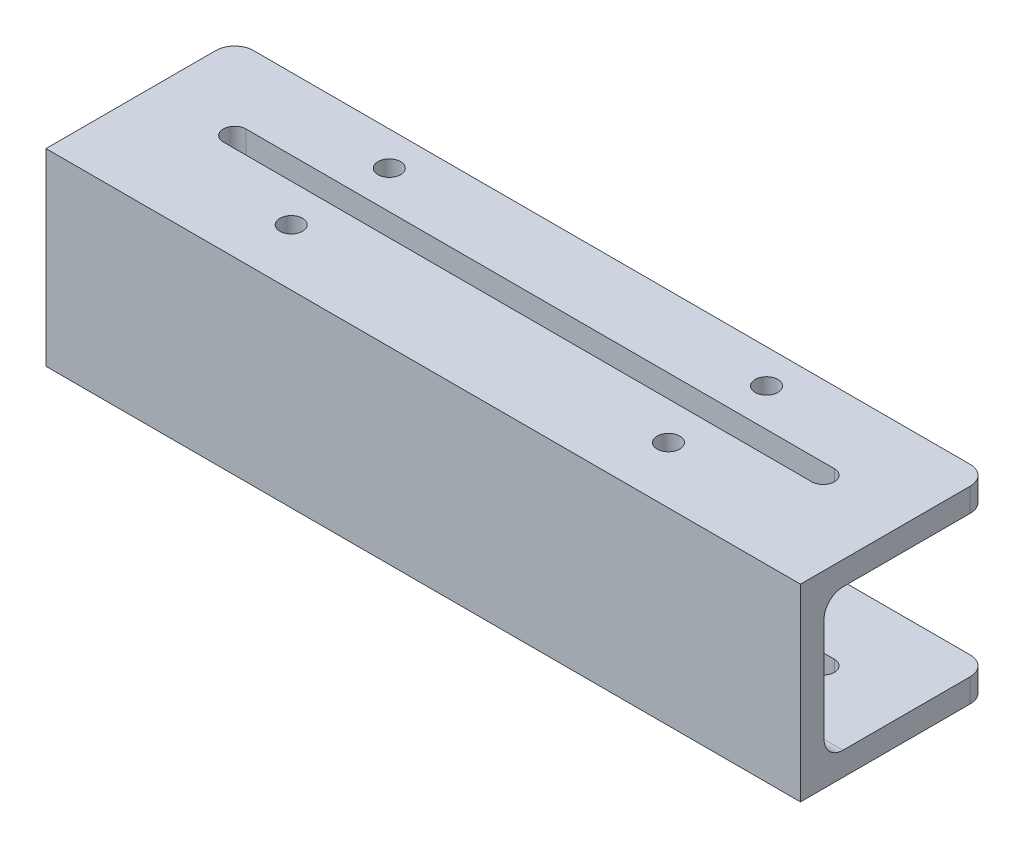
SolidWorks part; units mm, degrees
ref_plane "Front Plane" through (0, 0, 0) normal (0, 0, 1) x (1, 0, 0)
ref_plane "Top Plane" through (0, 0, 0) normal (0, 1, 0) x (1, 0, 0)
ref_plane "Right Plane" through (0, 0, 0) normal (1, 0, 0) x (0, 0, -1)
sketch "Sketch1" plane through (0, 0, 0) normal (0, 1, 0) x (1, 0, 0)
  line L1 (-44.7842, 12.9971) -> (56.8158, 12.9971)
  line L2 (-44.7842, 12.9971) -> (-44.7842, -12.4029)
  line L3 (-44.7842, -12.4029) -> (56.8158, -12.4029)
  line L4 (56.8158, 12.9971) -> (56.8158, -12.4029)
  dimension "D1" = 25.4
  dimension "D2" = 101.6
extrude "Boss-Extrude1" add sketch "Sketch1" along normal blind 25.4
sketch "Sketch2" plane through (0, 0, -12.9971) normal (0, 0, -1) x (-1, 0, 0)
  line L0 (-56.8158, 25.4) -> (-56.8158, 0) construction
  line L1 (-56.8158, 22.225) -> (44.7842, 22.225)
  line L2 (-56.8158, 22.225) -> (-56.8158, 3.175)
  line L3 (-56.8158, 3.175) -> (44.7842, 3.175)
  line L4 (44.7842, 22.225) -> (44.7842, 3.175)
  line L5 (44.7842, 25.4) -> (44.7842, 0) construction
  line L6 (-56.8158, 25.4) -> (44.7842, 25.4) construction
  line L7 (-56.8158, 0) -> (44.7842, 0) construction
  dimension "D1" = 3.175
  dimension "D2" = 3.175
extrude "Cut-Extrude1" cut sketch "Sketch2" against normal blind 22.225
sketch "Sketch4" plane through (0, 25.4, 0) normal (0, 1, 0) x (1, 0, 0)
  line L0 (56.8158, 12.9971) -> (-44.7842, 12.9971) construction
  line L1 (-44.7842, 12.9971) -> (-44.7842, -12.4029) construction
  line L2 (56.8158, -12.4029) -> (56.8158, 12.9971) construction
  line L3 (-33.6082, 0.2971) -> (45.6398, 0.2971)
  line L4 (-33.6082, 3.3451) -> (45.6398, 3.3451)
  arc A0 (-33.6082, 3.3451) -> (-33.6082, 0.2971) centre (-33.6082, 1.8211) ccw
  arc A1 (45.6398, 0.2971) -> (45.6398, 3.3451) centre (45.6398, 1.8211) ccw
  dimension "D1" = 3.048
  dimension "D4" = 3.048
  dimension "D2" = 11.176
  dimension "D3" = 11.176
  dimension "D5" = 11.176
  dimension "D6" = 11.176
extrude "Cut-Extrude2" cut sketch "Sketch4" against normal blind 25.4
sketch "Sketch5" plane through (0, 25.4, 0) normal (0, 1, 0) x (1, 0, 0)
  line L0 (45.6398, 3.3451) -> (-33.6082, 3.3451) construction
  line L1 (-33.6082, 0.2971) -> (45.6398, 0.2971) construction
  line L2 (-44.7842, 12.9971) -> (-44.7842, -12.4029) construction
  line L3 (56.8158, -12.4029) -> (56.8158, 12.9971) construction
  circle A0 centre (-19.3842, 8.4251) radius 1.524
  circle A1 centre (-19.3842, -4.7829) radius 1.524
  circle A2 centre (31.4158, 8.4251) radius 1.524
  circle A3 centre (31.4158, -4.7829) radius 1.524
  dimension "D1" = 3.048
  dimension "D2" = 3.048
  dimension "D3" = 3.048
  dimension "D4" = 3.048
  dimension "D7" = 5.08
  dimension "D8" = 5.08
  dimension "D9" = 25.4
  dimension "D10" = 25.4
  dimension "D11" = 25.4
  dimension "D12" = 25.4
  dimension "D5" = 5.08
  dimension "D6" = 5.08
extrude "Cut-Extrude4" cut sketch "Sketch5" against normal blind 3.175
chamfer "Chamfer1" distance 0.762 angle 45 4 edges at (31.4158, 22.225, 6.3069) (31.4158, 22.225, -6.9011) (-19.3842, 22.225, 6.3069) (-19.3842, 22.225, -6.9011)
fillet "Fillet1" radius 2.54 2 edges at (6.0158, 22.225, 9.2279) (6.0158, 3.175, 9.2279)
fillet "Fillet2" radius 2.54 4 edges at (56.8158, 1.5875, -12.9971) (56.8158, 23.8125, -12.9971) (-44.7842, 1.5875, -12.9971) (-44.7842, 23.8125, -12.9971)
